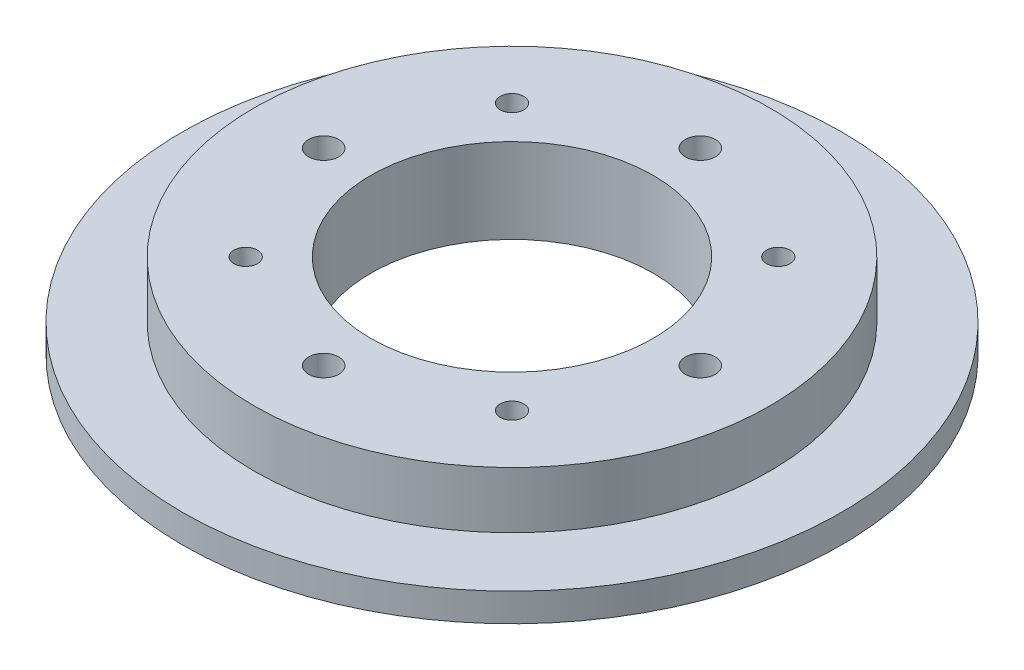
SolidWorks part; units mm, degrees
ref_plane "正面" through (0, 0, 0) normal (0, 0, 1) x (1, 0, 0)
ref_plane "平面" through (0, 0, 0) normal (0, 1, 0) x (1, 0, 0)
ref_plane "右側面" through (0, 0, 0) normal (1, 0, 0) x (0, 0, -1)
sketch "ｽｹｯﾁ1" plane through (0, 0, 0) normal (0, 1, 0) x (1, 0, 0)
  circle A0 centre (0, 0) radius 35
  dimension "D1" = 70
extrude "ﾎﾞｽ - 押し出し1" add sketch "ｽｹｯﾁ1" along normal blind 3 contours A0
sketch "ｽｹｯﾁ2" plane through (0, 3, 0) normal (0, 1, 0) x (1, 0, 0)
  circle A0 centre (0, 0) radius 27.4
  dimension "D1" = 54.8
extrude "ﾎﾞｽ - 押し出し2" add sketch "ｽｹｯﾁ2" along normal blind 6
sketch "ｽｹｯﾁ3" plane through (0, 9, 0) normal (0, 1, 0) x (1, 0, 0)
  line L0 (0, 20) -> (0, 0) construction
  line L1 (-20, 0) -> (0, 0) construction
  line L2 (0, 0) -> (0, -20) construction
  circle A0 centre (0, 20) radius 1.6
  circle A1 centre (20, 0) radius 1.6
  circle A2 centre (0, -20) radius 1.6
  circle A3 centre (-20, 0) radius 1.6
  dimension "D1" = 3.2
  dimension "D2" = 20
  dimension "D3" = 4
extrude "ｶｯﾄ - 押し出し1" cut sketch "ｽｹｯﾁ3" against normal through all
sketch "ｽｹｯﾁ4" plane through (0, 9, 0) normal (0, 1, 0) x (1, 0, 0)
  circle A0 centre (0, 0) radius 15
  dimension "D1" = 30
extrude "ｶｯﾄ - 押し出し2" cut sketch "ｽｹｯﾁ4" against normal through all
sketch "ｽｹｯﾁ5" plane through (0, 0, 0) normal (0, -1, 0) x (1, 0, 0)
  line L0 (-20, 0) -> (0, 0) construction
  line L1 (0, 0) -> (-14.1421, 14.1421) construction
  line L2 (-14.1421, -14.1421) -> (0, 0) construction
  line L3 (0, 0) -> (14.1421, -14.1421) construction
  line L4 (14.1421, 14.1421) -> (0, 0) construction
  circle A0 centre (-14.1421, 14.1421) radius 1.25
  circle A1 centre (14.1421, 14.1421) radius 1.25
  circle A2 centre (14.1421, -14.1421) radius 1.25
  circle A3 centre (-14.1421, -14.1421) radius 1.25
  dimension "D2" = 2.5
  dimension "D1" = 45
  dimension "D3" = 20
  dimension "D4" = 4
extrude "ｶｯﾄ - 押し出し3" cut sketch "ｽｹｯﾁ5" against normal through all
